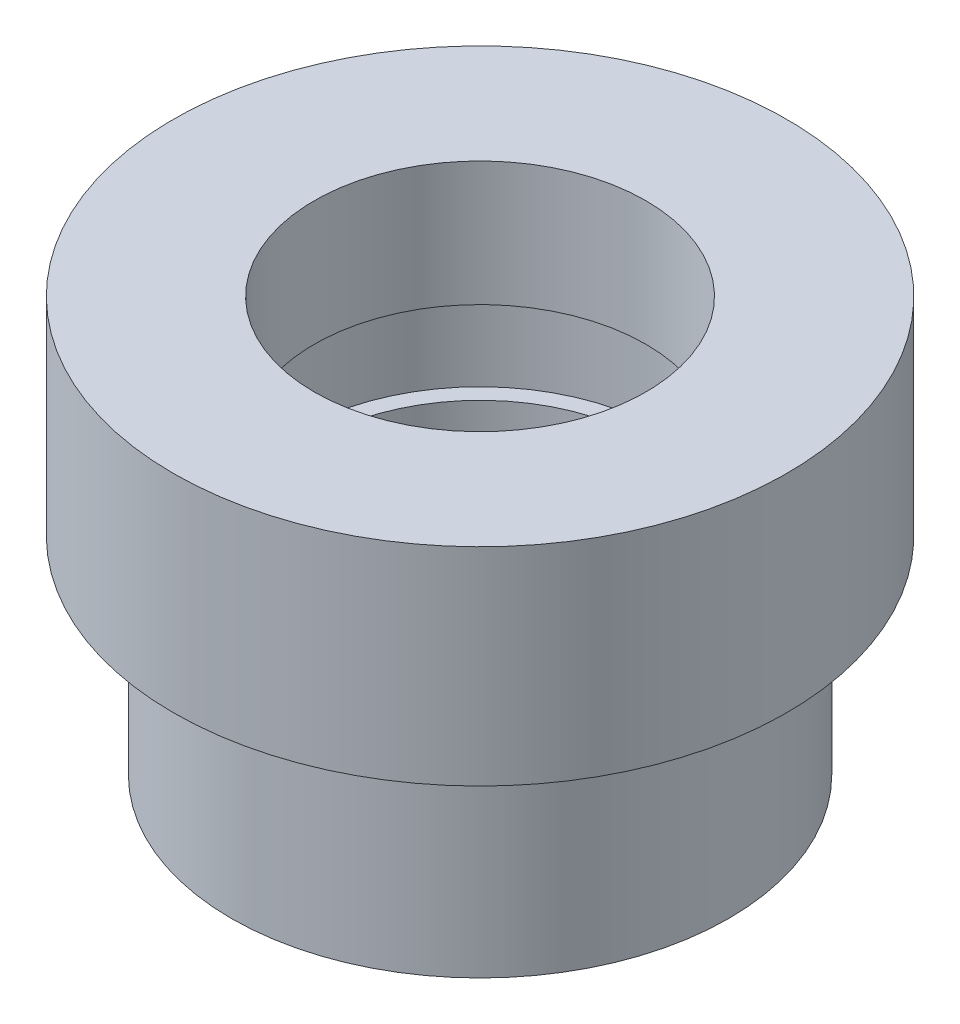
SolidWorks part; units mm, degrees
ref_plane "Front Plane" through (0, 0, 0) normal (0, 0, 1) x (1, 0, 0)
ref_plane "Top Plane" through (0, 0, 0) normal (0, 1, 0) x (1, 0, 0)
ref_plane "Right Plane" through (0, 0, 0) normal (1, 0, 0) x (0, 0, -1)
sketch "Sketch1" plane through (0, 0, 0) normal (0, 0, 1) x (1, 0, 0)
  line L0 (0, 23.7379) -> (0, -25) construction
  line L1 (-37, 50) -> (-20, 50)
  line L2 (-20, 50) -> (-20, 35)
  line L3 (-20, 35) -> (-22, 35)
  line L4 (-22, 35) -> (-22, 25)
  line L5 (-22, 25) -> (-20, 25)
  line L6 (-20, 25) -> (-20, 0)
  line L7 (-20, 0) -> (-30, 0)
  line L8 (-30, 0) -> (-30, 25)
  line L9 (-30, 25) -> (-37, 25)
  line L10 (-37, 25) -> (-37, 50)
  line L11 (-54.2063, 0) -> (8.267, 0) construction
  dimension "D1" = 20
  dimension "D2" = 17
  dimension "D3" = 50
  dimension "D4" = 2
  dimension "D5" = 25
  dimension "D6" = 10
  dimension "D7" = 10
revolve "Revolve1" add sketch "Sketch1" angle 360 mid plane about L0
